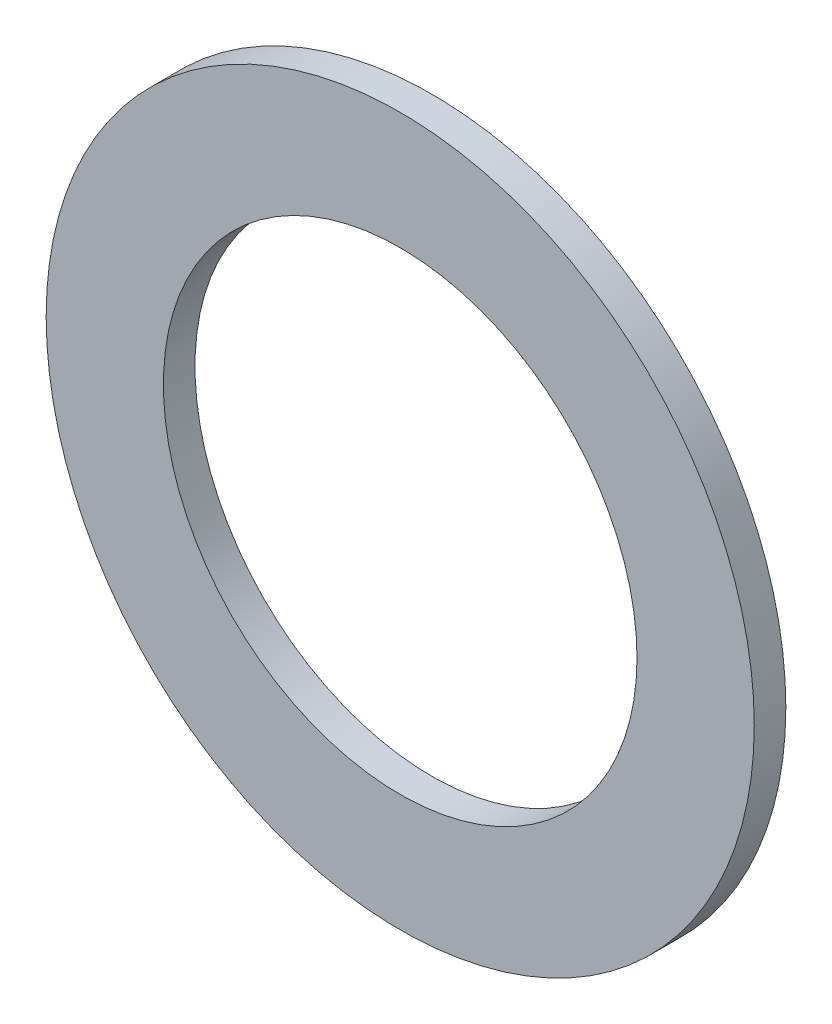
SolidWorks part; units mm, degrees
ref_plane "Front Plane" through (0, 0, 0) normal (0, 0, 1) x (1, 0, 0)
ref_plane "Top Plane" through (0, 0, 0) normal (0, 1, 0) x (1, 0, 0)
ref_plane "Right Plane" through (0, 0, 0) normal (1, 0, 0) x (0, 0, -1)
sketch "Sketch1" plane through (0, 0, 0) normal (0, 0, 1) x (1, 0, 0)
  circle A0 centre (0, 0) radius 75
  circle A1 centre (0, 0) radius 112.14
  dimension "D1" = 224.28
  dimension "D2" = 150
extrude "Boss-Extrude1" add sketch "Sketch1" against normal blind 10
